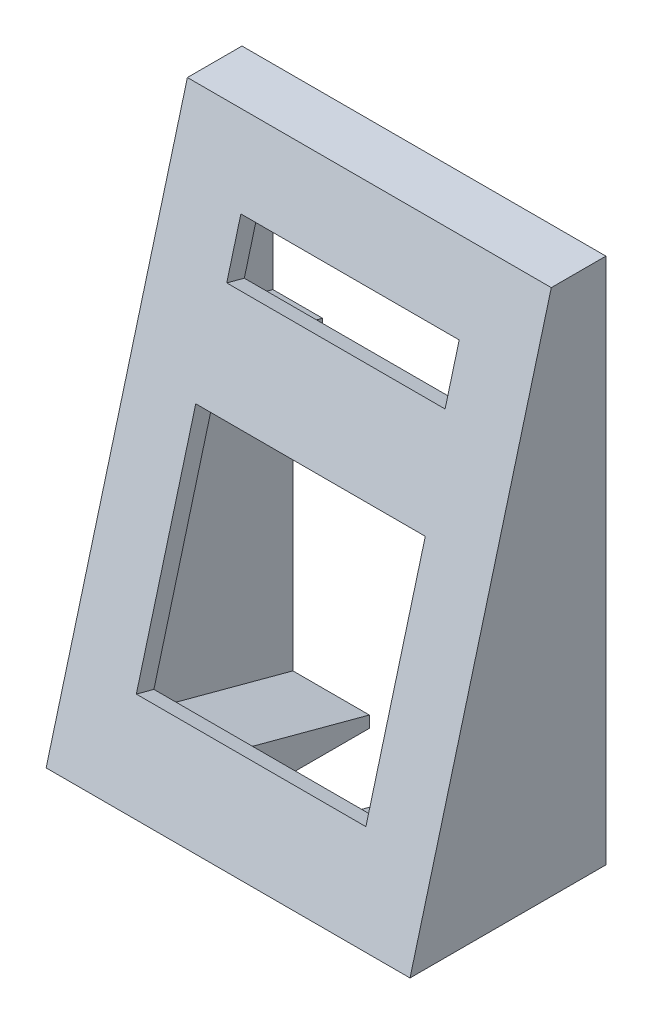
SolidWorks part; units mm, degrees
ref_plane "Front Plane" through (0, 0, 0) normal (0, 0, 1) x (1, 0, 0)
ref_plane "Top Plane" through (0, 0, 0) normal (0, 1, 0) x (1, 0, 0)
ref_plane "Right Plane" through (0, 0, 0) normal (1, 0, 0) x (0, 0, -1)
sketch "Sketch1" plane through (0, 0, 0) normal (1, 0, 0) x (0, 0, -1)
  line L0 (0, 0) -> (0, 144.8889)
  line L1 (0, 144.8889) -> (-38.8229, 0)
  line L2 (-38.8229, 0) -> (0, 0)
  dimension "D1" = 15
  dimension "D2" = 150
extrude "Boss-Extrude1" add sketch "Sketch1" along normal mid plane 100
sketch "Sketch5" plane through (0, 0, 0) normal (1, 0, 0) x (0, 0, -1)
  line L0 (0, 144.8889) -> (15, 144.8889)
  line L1 (15, 144.8889) -> (15, 0)
  line L2 (15, 0) -> (0, 0)
  line L3 (0, 0) -> (0, 144.8889)
  dimension "D1" = 15
extrude "Boss-Extrude2" add sketch "Sketch5" along normal mid plane 100
sketch "Sketch2" plane through (0, 9.7057, 36.2222) normal (0, 0.2588, 0.9659) x (1, 0, 0)
  line L1 (-15, 9.9519) -> (15, 9.9519)
  line L2 (-15, 9.9519) -> (-15, -5.0481)
  line L3 (-15, -5.0481) -> (15, -5.0481)
  line L4 (15, 9.9519) -> (15, -5.0481)
  line L5 (-15, 9.9519) -> (15, -5.0481) construction
  line L6 (-15, -5.0481) -> (15, 9.9519) construction
  line L7 (-36, 84.9519) -> (36, 84.9519)
  line L8 (-36, 84.9519) -> (-36, 6.9519)
  line L9 (-36, 6.9519) -> (36, 6.9519)
  line L10 (36, 84.9519) -> (36, 6.9519)
  line L11 (-36, 84.9519) -> (36, 6.9519) construction
  line L12 (-36, 6.9519) -> (36, 84.9519) construction
  line L14 (-40, 129.9519) -> (40, 129.9519)
  line L15 (-40, 129.9519) -> (-40, 93.9519)
  line L16 (-40, 93.9519) -> (40, 93.9519)
  line L17 (40, 129.9519) -> (40, 93.9519)
  line L18 (-40, 129.9519) -> (40, 93.9519) construction
  line L19 (-40, 93.9519) -> (40, 129.9519) construction
  line L20 (50, 139.9519) -> (-50, 139.9519) construction
  point P0 (0, 2.4519)
  point P6 (0, 45.9519)
  point P16 (0, 111.9519)
  dimension "D1" = 15
  dimension "D2" = 30
  dimension "D3" = 78
  dimension "D4" = 72
  dimension "D5" = 55
  dimension "D6" = 3
  dimension "D7" = 36
  dimension "D8" = 80
  dimension "D9" = 10
sketch "Sketch3" plane through (0, 9.7057, 36.2222) normal (0, 0.2588, 0.9659) x (1, 0, 0)
  line L1 (-31.541, 77.4929) -> (31.541, 77.4929)
  line L2 (-31.541, 77.4929) -> (-31.541, 14.4109)
  line L3 (-31.541, 14.4109) -> (31.541, 14.4109)
  line L4 (31.541, 77.4929) -> (31.541, 14.4109)
  line L5 (-31.541, 77.4929) -> (31.541, 14.4109) construction
  line L6 (-31.541, 14.4109) -> (31.541, 77.4929) construction
  line L9 (-30, 119.4519) -> (30, 119.4519)
  line L10 (-30, 119.4519) -> (-30, 104.4519)
  line L11 (-30, 104.4519) -> (30, 104.4519)
  line L12 (30, 119.4519) -> (30, 104.4519)
  line L13 (-30, 119.4519) -> (30, 104.4519) construction
  line L14 (-30, 104.4519) -> (30, 119.4519) construction
  point P0 (0, 45.9519)
  point P5 (0, 111.9519)
  dimension "D1" = 63.082
  dimension "D2" = 15
  dimension "D3" = 60
extrude "Cut-Extrude1" cut sketch "Sketch3" against normal through all
sketch "Sketch4" plane through (0, 9.7057, 36.2222) normal (0, 0.2588, 0.9659) x (1, 0, 0)
  line L0 (-36, 84.9519) -> (36, 6.9519) construction
  line L1 (-36, 84.9519) -> (36, 84.9519)
  line L2 (-36, 84.9519) -> (-36, 6.9519)
  line L3 (-36, 6.9519) -> (-15, 6.9519)
  line L4 (36, 84.9519) -> (36, 6.9519)
  line L5 (-36, 84.9519) -> (36, 6.9519) construction
  line L6 (-36, 6.9519) -> (36, 84.9519) construction
  line L7 (-15, 6.9519) -> (-15, -5.0481)
  line L8 (-37.5, 125.4519) -> (37.5, 125.4519)
  line L9 (-37.5, 125.4519) -> (-37.5, 98.4519)
  line L10 (-37.5, 98.4519) -> (37.5, 98.4519)
  line L11 (37.5, 125.4519) -> (37.5, 98.4519)
  line L12 (-37.5, 125.4519) -> (37.5, 98.4519) construction
  line L13 (-37.5, 98.4519) -> (37.5, 125.4519) construction
  line L14 (-15, 9.9519) -> (-15, -5.0481) construction
  line L15 (-15, -5.0481) -> (15, -5.0481)
  line L16 (15, -5.0481) -> (15, 6.9519)
  line L17 (15, 9.9519) -> (15, -5.0481) construction
  line L18 (15, 6.9519) -> (36, 6.9519)
  point P0 (0, 45.9519)
  point P8 (0, 111.9519)
  dimension "D1" = 27
  dimension "D2" = 75
extrude "Cut-Extrude2" cut sketch "Sketch4" against normal through all from offset 5 offset against normal yes
sketch "Sketch6" plane through (0, 9.7057, 36.2222) normal (0, 0.2588, 0.9659) x (1, 0, 0)
  line L0 (-40, 129.9519) -> (40, 93.9519) construction
  line L1 (-41.5, 131.9519) -> (41.5, 131.9519)
  line L2 (-41.5, 131.9519) -> (-41.5, 91.9519)
  line L3 (-41.5, 91.9519) -> (41.5, 91.9519)
  line L4 (41.5, 131.9519) -> (41.5, 91.9519)
  line L5 (-41.5, 131.9519) -> (41.5, 91.9519) construction
  line L6 (-41.5, 91.9519) -> (41.5, 131.9519) construction
  point P0 (0, 111.9519)
  dimension "D1" = 40
  dimension "D2" = 83
extrude "Cut-Extrude3" cut sketch "Sketch6" against normal blind 100 from offset 14 offset against normal yes
sketch "Sketch7" plane through (0, 6.0822, 22.6993) normal (0, -0.2588, -0.9659) x (-1, 0, 0)
  line L0 (40, 129.9519) -> (-40, 129.9519) construction
  line L1 (40, 129.9519) -> (40, 93.9519) construction
  line L2 (0, 49.5) -> (0, -49.5) construction
  line L3 (0, 111.9519) -> (40, 111.9519) construction
  line L4 (40, 129.9519) -> (-40, 93.9519) construction
  circle A0 centre (37.5, 127.4519) radius 1.5
  circle A1 centre (-37.5, 127.4519) radius 1.5
  circle A2 centre (37.5, 96.4519) radius 1.5
  circle A3 centre (-37.5, 96.4519) radius 1.5
  dimension "D1" = 2.5
  dimension "D3" = 3
  dimension "D2" = 2.5
extrude "Cut-Extrude4" cut sketch "Sketch7" against normal blind 10
sketch "Sketch8" plane through (0, 6.0822, 22.6993) normal (0, -0.2588, -0.9659) x (-1, 0, 0)
  line L0 (41.5, 91.9519) -> (-41.5, 91.9519) construction
  line L1 (-27.845, 98.9519) -> (27.845, 98.9519)
  line L2 (-27.845, 98.9519) -> (-27.845, 84.9519)
  line L3 (-27.845, 84.9519) -> (27.845, 84.9519)
  line L4 (27.845, 98.9519) -> (27.845, 84.9519)
  line L5 (-27.845, 98.9519) -> (27.845, 84.9519) construction
  line L6 (-27.845, 84.9519) -> (27.845, 98.9519) construction
  line L7 (-36, 84.9519) -> (36, 84.9519) construction
  point P0 (0, 91.9519)
extrude "Cut-Extrude5" cut sketch "Sketch8" along normal through all
